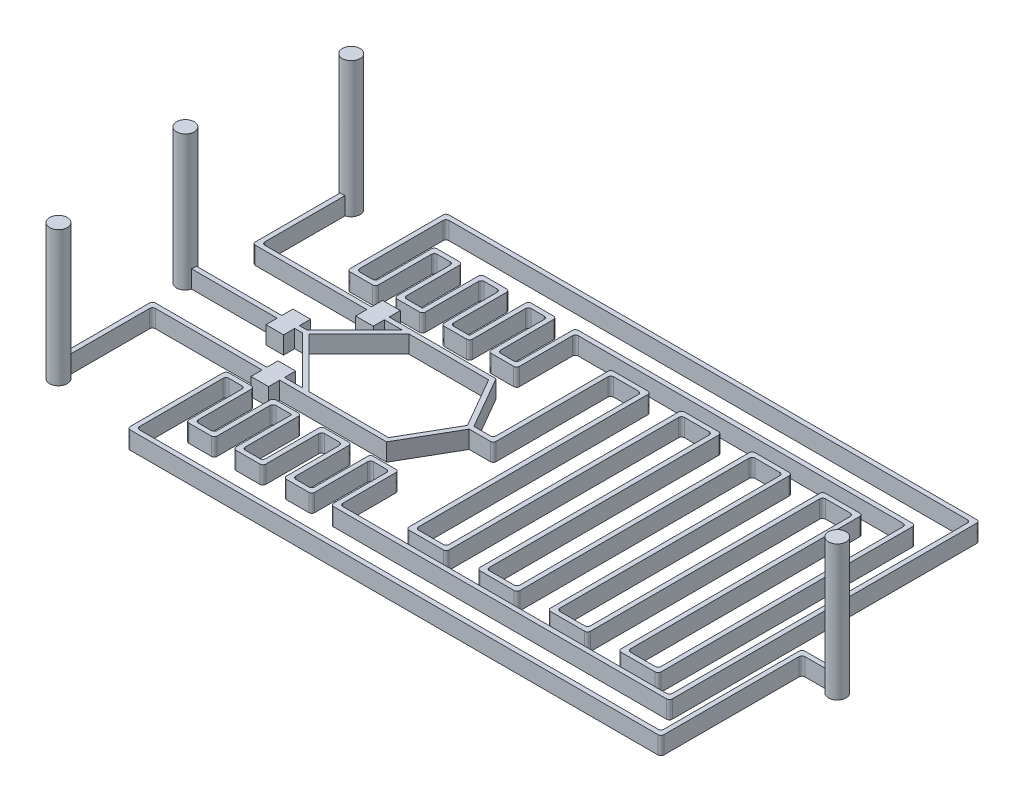
SolidWorks part; units mm, degrees
ref_plane "Front Plane" through (0, 0, 0) normal (0, 0, 1) x (1, 0, 0)
ref_plane "Top Plane" through (0, 0, 0) normal (0, 1, 0) x (1, 0, 0)
ref_plane "Right Plane" through (0, 0, 0) normal (1, 0, 0) x (0, 0, -1)
sketch "Sketch3" plane through (0, 0, 0) normal (0, 1, 0) x (1, 0, 0)
  line L0 (-37.0734, 0) -> (26.9266, 0) construction
  line L1 (19.9441, -2.9275) -> (19.9441, -14.4275)
  line L35 (-15.5329, 9.0171) -> (-23.3329, 9.0171) construction
  line L68 (-24.0079, 5.6024) -> (-22.5079, 5.6024)
  line L69 (-24.0079, 5.6024) -> (-24.0079, 4.6524)
  line L70 (-24.0079, 3.3024) -> (-22.5079, 3.3024)
  line L71 (-22.5079, 5.6024) -> (-22.5079, 4.6524)
  line L72 (-24.0079, 4.2524) -> (-24.0079, 3.3024)
  line L73 (-22.5079, 4.2524) -> (-22.5079, 3.3024)
  line L74 (-24.0079, -3.3024) -> (-22.5079, -3.3024)
  line L75 (-24.0079, -3.3024) -> (-24.0079, -4.2524)
  line L76 (-24.0079, -5.6024) -> (-22.5079, -5.6024)
  line L77 (-22.5079, -3.3024) -> (-22.5079, -4.2524)
  line L78 (-22.5079, -4.6524) -> (-22.5079, -5.6024)
  line L79 (-24.0079, -4.6524) -> (-24.0079, -5.6024)
  line L80 (-22.5079, -4.2524) -> (-20.9907, -4.2524)
  line L81 (-7.0734, 0) -> (26.9266, 0) construction
  line L82 (-13.4155, 4.6524) -> (-10.8448, 0.2)
  line L83 (-27.1856, 1.15) -> (-25.6856, 1.15)
  line L84 (-27.1856, 1.15) -> (-27.1856, 0.2)
  line L85 (-27.1856, -1.15) -> (-25.6856, -1.15)
  line L86 (-25.6856, 1.15) -> (-25.6856, 0.2)
  line L89 (-33.0809, 4.6524) -> (-24.0079, 4.6524)
  line L90 (-33.3309, 4.9024) -> (-33.3309, 11.7296)
  line L91 (-33.3309, -4.9024) -> (-33.3309, -11.7296)
  line L92 (-33.0809, -4.6524) -> (-24.0079, -4.6524)
  line L93 (-13.4155, -4.6524) -> (-10.8448, -0.2)
  line L94 (-10.8448, -0.2) -> (-9.05, -0.2)
  line L95 (-8.8, 0.05) -> (-8.8, 9.55)
  line L96 (-8.55, 9.8) -> (-6.45, 9.8)
  line L97 (-6.2, 9.55) -> (-6.2, 0)
  line L98 (-6.2, 0) -> (-6.2, -9.95)
  line L99 (-5.95, -10.2) -> (-3.05, -10.2)
  line L100 (-2.8, -9.95) -> (-2.8, 9.5671)
  line L101 (-2.55, 9.8171) -> (-0.45, 9.8171)
  line L102 (-0.2, 9.5671) -> (-0.2, -9.9275)
  line L103 (0.05, -10.1775) -> (2.95, -10.1775)
  line L104 (3.2, -9.9275) -> (3.2, 9.5725)
  line L105 (3.45, 9.8225) -> (5.55, 9.8225)
  line L106 (5.8, 9.5725) -> (5.8, -9.9275)
  line L107 (6.05, -10.1775) -> (8.95, -10.1775)
  line L108 (9.2, -9.9275) -> (9.2, 9.5725)
  line L109 (9.45, 9.8225) -> (11.55, 9.8225)
  line L110 (11.8, 9.5725) -> (11.8, -9.9275)
  line L111 (12.05, -10.1775) -> (14.95, -10.1775)
  line L112 (15.2, -9.9275) -> (15.2, 0)
  line L113 (15.2, 0) -> (15.2, 11.4671)
  line L114 (14.95, 11.7171) -> (-13.4809, 11.7171)
  line L115 (-13.7309, 11.4671) -> (-13.7309, 6.9671)
  line L116 (-13.9809, 6.7171) -> (-15.0829, 6.7171)
  line L117 (-15.3329, 6.9671) -> (-15.3329, 11.4671)
  line L118 (-15.5829, 11.7171) -> (-17.4829, 11.7171)
  line L119 (-17.7329, 11.4671) -> (-17.7329, 6.7171)
  line L120 (-17.7329, 6.7171) -> (-19.0829, 6.7171)
  line L121 (-19.3329, 6.9671) -> (-19.3329, 11.4671)
  line L122 (-19.5829, 11.7171) -> (-21.4829, 11.7171)
  line L123 (-21.7329, 11.4671) -> (-21.7329, 6.7171)
  line L124 (-21.7329, 6.7171) -> (-23.0829, 6.7171)
  line L125 (-23.3329, 6.9671) -> (-23.3329, 11.4671)
  line L126 (-23.5829, 11.7171) -> (-25.4829, 11.7171)
  line L127 (-25.7329, 11.4671) -> (-25.7329, 6.9671)
  line L128 (-25.9829, 6.7171) -> (-27.0829, 6.7171)
  line L129 (-27.3329, 6.9671) -> (-27.3329, 14.0671)
  line L130 (-27.0829, 14.3171) -> (17.0171, 14.3171)
  line L131 (17.2671, 14.0671) -> (17.2671, -11.0275)
  line L132 (17.0171, -11.2775) -> (-10.5103, -11.2775)
  line L133 (-10.7603, -11.0275) -> (-10.7603, -6.5275)
  line L134 (-11.0103, -6.2775) -> (-12.9103, -6.2775)
  line L135 (-13.1603, -6.5275) -> (-13.1603, -11.0275)
  line L136 (-13.4103, -11.2775) -> (-14.5103, -11.2775)
  line L137 (-14.7603, -11.0275) -> (-14.7603, -6.5275)
  line L138 (-15.0103, -6.2775) -> (-17.0705, -6.2775)
  line L139 (-17.3205, -6.5275) -> (-17.3205, -11.0275)
  line L140 (-17.5705, -11.2775) -> (-18.8059, -11.2775)
  line L141 (-19.0559, -11.0275) -> (-19.0559, -6.5275)
  line L142 (-19.3059, -6.2775) -> (-21.2059, -6.2775)
  line L143 (-21.4559, -6.5275) -> (-21.4559, -11.0275)
  line L144 (-21.7059, -11.2775) -> (-22.8059, -11.2775)
  line L145 (-23.0559, -11.0275) -> (-23.0559, -6.5275)
  line L146 (-23.3059, -6.2775) -> (-25.2059, -6.2775)
  line L147 (-25.4559, -6.5275) -> (-25.4559, -14.4275)
  line L148 (-25.2059, -14.6775) -> (19.6941, -14.6775)
  line L149 (-24.6775, 0) -> (-20.425, 4.2524)
  line L150 (-25.0432, -0.2) -> (-20.9907, -4.2524)
  line L151 (-13.6464, 4.2524) -> (-11.1913, 0)
  line L152 (-33.4809, 4.2524) -> (-24.0079, 4.2524)
  line L153 (-33.7309, 4.5024) -> (-33.7309, 11.7296)
  line L154 (-33.7309, -4.5024) -> (-33.7309, -11.7296)
  line L155 (-33.4809, -4.2524) -> (-24.0079, -4.2524)
  line L156 (-13.6464, -4.2524) -> (-11.1913, 0)
  line L157 (-10.8448, 0.2) -> (-9.45, 0.2)
  line L158 (-9.2, 0.45) -> (-9.2, 9.95)
  line L159 (-8.95, 10.2) -> (-6.05, 10.2)
  line L160 (-5.8, 9.95) -> (-5.8, 0)
  line L161 (-5.8, 0) -> (-5.8, -9.55)
  line L162 (-5.55, -9.8) -> (-3.45, -9.8)
  line L163 (-3.2, -9.55) -> (-3.2, 9.9671)
  line L164 (-2.95, 10.2171) -> (-0.05, 10.2171)
  line L165 (0.2, 9.9671) -> (0.2, -9.5275)
  line L166 (0.45, -9.7775) -> (2.55, -9.7775)
  line L167 (2.8, -9.5275) -> (2.8, 9.9725)
  line L168 (3.05, 10.2225) -> (5.95, 10.2225)
  line L169 (6.2, 9.9725) -> (6.2, -9.5275)
  line L170 (6.45, -9.7775) -> (8.55, -9.7775)
  line L171 (8.8, -9.5275) -> (8.8, 9.9725)
  line L172 (9.05, 10.2225) -> (11.95, 10.2225)
  line L173 (12.2, 9.9725) -> (12.2, -9.5275)
  line L174 (12.45, -9.7775) -> (14.55, -9.7775)
  line L175 (14.8, -9.5275) -> (14.8, 0)
  line L176 (14.8, 0) -> (14.8, 11.0671)
  line L177 (14.55, 11.3171) -> (-13.0809, 11.3171)
  line L178 (-13.3309, 11.0671) -> (-13.3309, 6.5671)
  line L179 (-13.5809, 6.3171) -> (-15.4829, 6.3171)
  line L180 (-15.7329, 6.5671) -> (-15.7329, 11.0671)
  line L181 (-15.9829, 11.3171) -> (-17.0829, 11.3171)
  line L182 (-17.3329, 11.0671) -> (-17.3329, 6.5671)
  line L183 (-17.5829, 6.3171) -> (-19.4829, 6.3171)
  line L184 (-19.7329, 6.5671) -> (-19.7329, 11.0671)
  line L185 (-19.9829, 11.3171) -> (-21.0829, 11.3171)
  line L186 (-21.3329, 11.0671) -> (-21.3329, 6.5671)
  line L187 (-21.5829, 6.3171) -> (-23.4829, 6.3171)
  line L188 (-23.7329, 6.5671) -> (-23.7329, 11.0671)
  line L189 (-23.9829, 11.3171) -> (-25.0829, 11.3171)
  line L190 (-25.3329, 11.0671) -> (-25.3329, 6.5671)
  line L191 (-25.5829, 6.3171) -> (-27.4829, 6.3171)
  line L192 (-27.7329, 6.5671) -> (-27.7329, 14.4671)
  line L193 (-27.4829, 14.7171) -> (17.4171, 14.7171)
  line L194 (17.6671, 14.4671) -> (17.6671, -11.4275)
  line L195 (17.4171, -11.6775) -> (-10.9103, -11.6775)
  line L196 (-11.1603, -11.4275) -> (-11.1603, -6.9275)
  line L197 (-11.4103, -6.6775) -> (-12.5103, -6.6775)
  line L198 (-12.7603, -6.9275) -> (-12.7603, -11.4275)
  line L199 (-13.0103, -11.6775) -> (-14.9103, -11.6775)
  line L200 (-15.1603, -11.4275) -> (-15.1603, -6.9275)
  line L201 (-15.4103, -6.6775) -> (-16.6705, -6.6775)
  line L202 (-16.9205, -6.9275) -> (-16.9205, -11.4275)
  line L203 (-17.1705, -11.6775) -> (-19.2059, -11.6775)
  line L204 (-19.4559, -11.4275) -> (-19.4559, -6.6775)
  line L205 (-19.4559, -6.6775) -> (-20.8059, -6.6775)
  line L206 (-21.0559, -6.9275) -> (-21.0559, -11.4275)
  line L207 (-21.3059, -11.6775) -> (-23.2059, -11.6775)
  line L208 (-23.4559, -11.4275) -> (-23.4559, -6.9275)
  line L209 (-23.7059, -6.6775) -> (-24.8059, -6.6775)
  line L210 (-25.0559, -6.9275) -> (-25.0559, -14.0275)
  line L211 (-24.8059, -14.2775) -> (19.2941, -14.2775)
  line L212 (-25.0432, 0.2) -> (-20.9907, 4.2524)
  line L213 (-24.6775, 0) -> (-20.425, -4.2524)
  line L217 (-25.6856, -0.2) -> (-25.0432, -0.2)
  line L218 (-27.1856, 0.2) -> (-34.4627, 0.2)
  line L220 (20.1941, -2.6775) -> (22.0212, -2.6775)
  line L221 (-25.6856, 0.2) -> (-25.0432, 0.2)
  line L222 (-27.1856, -0.2) -> (-34.4627, -0.2)
  line L223 (19.5441, -14.0275) -> (19.5441, -2.5275)
  line L224 (19.7941, -2.2775) -> (22.0212, -2.2775)
  line L229 (-22.5079, 4.6524) -> (-13.4155, 4.6524)
  line L231 (-22.5079, 4.2524) -> (-20.9907, 4.2524)
  line L233 (-20.425, 4.2524) -> (-13.6464, 4.2524)
  line L235 (-27.1856, -0.2) -> (-27.1856, -1.15)
  line L236 (-25.6856, -0.2) -> (-25.6856, -1.15)
  line L239 (-22.5079, -4.6524) -> (-13.4155, -4.6524)
  line L242 (-20.425, -4.2524) -> (-13.6464, -4.2524)
  arc A0 (-33.3309, 11.7296) -> (-33.7309, 11.7296) centre (-33.5309, 12.4524) ccw
  arc A1 (-34.4627, 0.2) -> (-34.4627, -0.2) centre (-35.1856, 0) ccw
  arc A2 (-33.7309, -11.7296) -> (-33.3309, -11.7296) centre (-33.5309, -12.4524) ccw
  arc A3 (22.0212, -2.6775) -> (22.0212, -2.2775) centre (22.7441, -2.4775) ccw
  arc A4 (11.8, -9.9275) -> (12.05, -10.1775) centre (12.05, -9.9275) ccw
  arc A5 (12.2, -9.5275) -> (12.45, -9.7775) centre (12.45, -9.5275) ccw
  arc A6 (14.95, -10.1775) -> (15.2, -9.9275) centre (14.95, -9.9275) ccw
  arc A7 (14.55, -9.7775) -> (14.8, -9.5275) centre (14.55, -9.5275) ccw
  arc A8 (19.5441, -2.5275) -> (19.7941, -2.2775) centre (19.7941, -2.5275) cw
  arc A9 (19.9441, -2.9275) -> (20.1941, -2.6775) centre (20.1941, -2.9275) cw
  arc A10 (17.6671, -11.4275) -> (17.4171, -11.6775) centre (17.4171, -11.4275) cw
  arc A11 (17.2671, -11.0275) -> (17.0171, -11.2775) centre (17.0171, -11.0275) cw
  arc A12 (17.4171, 14.7171) -> (17.6671, 14.4671) centre (17.4171, 14.4671) cw
  arc A13 (17.0171, 14.3171) -> (17.2671, 14.0671) centre (17.0171, 14.0671) cw
  arc A14 (15.2, 11.4671) -> (14.95, 11.7171) centre (14.95, 11.4671) ccw
  arc A15 (14.8, 11.0671) -> (14.55, 11.3171) centre (14.55, 11.0671) ccw
  arc A16 (-13.4809, 11.7171) -> (-13.7309, 11.4671) centre (-13.4809, 11.4671) ccw
  arc A17 (-13.0809, 11.3171) -> (-13.3309, 11.0671) centre (-13.0809, 11.0671) ccw
  arc A18 (-13.3309, 6.5671) -> (-13.5809, 6.3171) centre (-13.5809, 6.5671) cw
  arc A19 (-13.7309, 6.9671) -> (-13.9809, 6.7171) centre (-13.9809, 6.9671) cw
  arc A20 (-15.7329, 11.0671) -> (-15.9829, 11.3171) centre (-15.9829, 11.0671) ccw
  arc A21 (-15.3329, 11.4671) -> (-15.5829, 11.7171) centre (-15.5829, 11.4671) ccw
  arc A22 (-17.0829, 11.3171) -> (-17.3329, 11.0671) centre (-17.0829, 11.0671) ccw
  arc A23 (-17.4829, 11.7171) -> (-17.7329, 11.4671) centre (-17.4829, 11.4671) ccw
  arc A24 (-19.3329, 11.4671) -> (-19.5829, 11.7171) centre (-19.5829, 11.4671) ccw
  arc A25 (-19.7329, 11.0671) -> (-19.9829, 11.3171) centre (-19.9829, 11.0671) ccw
  arc A26 (-21.0829, 11.3171) -> (-21.3329, 11.0671) centre (-21.0829, 11.0671) ccw
  arc A27 (-21.4829, 11.7171) -> (-21.7329, 11.4671) centre (-21.4829, 11.4671) ccw
  arc A28 (-23.3329, 11.4671) -> (-23.5829, 11.7171) centre (-23.5829, 11.4671) ccw
  arc A29 (-23.7329, 11.0671) -> (-23.9829, 11.3171) centre (-23.9829, 11.0671) ccw
  arc A30 (-25.0829, 11.3171) -> (-25.3329, 11.0671) centre (-25.0829, 11.0671) ccw
  arc A31 (-25.4829, 11.7171) -> (-25.7329, 11.4671) centre (-25.4829, 11.4671) ccw
  arc A32 (-25.9829, 6.7171) -> (-25.7329, 6.9671) centre (-25.9829, 6.9671) ccw
  arc A33 (-25.3329, 6.5671) -> (-25.5829, 6.3171) centre (-25.5829, 6.5671) cw
  arc A34 (-33.7309, -4.5024) -> (-33.4809, -4.2524) centre (-33.4809, -4.5024) cw
  arc A35 (-33.3309, -4.9024) -> (-33.0809, -4.6524) centre (-33.0809, -4.9024) cw
  arc A36 (-14.9103, -11.6775) -> (-15.1603, -11.4275) centre (-14.9103, -11.4275) cw
  arc A37 (-14.5103, -11.2775) -> (-14.7603, -11.0275) centre (-14.5103, -11.0275) cw
  arc A38 (-13.4103, -11.2775) -> (-13.1603, -11.0275) centre (-13.4103, -11.0275) ccw
  arc A39 (-13.0103, -11.6775) -> (-12.7603, -11.4275) centre (-13.0103, -11.4275) ccw
  arc A40 (-10.9103, -11.6775) -> (-11.1603, -11.4275) centre (-10.9103, -11.4275) cw
  arc A41 (-10.5103, -11.2775) -> (-10.7603, -11.0275) centre (-10.5103, -11.0275) cw
  arc A42 (-25.4559, -6.5275) -> (-25.2059, -6.2775) centre (-25.2059, -6.5275) cw
  arc A43 (-25.0559, -6.9275) -> (-24.8059, -6.6775) centre (-24.8059, -6.9275) cw
  arc A44 (-23.0559, -6.5275) -> (-23.3059, -6.2775) centre (-23.3059, -6.5275) ccw
  arc A45 (-23.4559, -6.9275) -> (-23.7059, -6.6775) centre (-23.7059, -6.9275) ccw
  arc A46 (-11.1603, -6.9275) -> (-11.4103, -6.6775) centre (-11.4103, -6.9275) ccw
  arc A47 (-10.7603, -6.5275) -> (-11.0103, -6.2775) centre (-11.0103, -6.5275) ccw
  arc A48 (-13.1603, -6.5275) -> (-12.9103, -6.2775) centre (-12.9103, -6.5275) cw
  arc A49 (-12.7603, -6.9275) -> (-12.5103, -6.6775) centre (-12.5103, -6.9275) cw
  arc A50 (-14.7603, -6.5275) -> (-15.0103, -6.2775) centre (-15.0103, -6.5275) ccw
  arc A51 (-15.4103, -6.6775) -> (-15.1603, -6.9275) centre (-15.4103, -6.9275) cw
  arc A52 (-16.9205, -6.9275) -> (-16.6705, -6.6775) centre (-16.6705, -6.9275) cw
  arc A53 (-17.3205, -6.5275) -> (-17.0705, -6.2775) centre (-17.0705, -6.5275) cw
  arc A54 (-19.0559, -6.5275) -> (-19.3059, -6.2775) centre (-19.3059, -6.5275) ccw
  arc A55 (-21.4559, -6.5275) -> (-21.2059, -6.2775) centre (-21.2059, -6.5275) cw
  arc A56 (-21.0559, -6.9275) -> (-20.8059, -6.6775) centre (-20.8059, -6.9275) cw
  arc A57 (-23.2059, -11.6775) -> (-23.4559, -11.4275) centre (-23.2059, -11.4275) cw
  arc A58 (-22.8059, -11.2775) -> (-23.0559, -11.0275) centre (-22.8059, -11.0275) cw
  arc A59 (-21.4559, -11.0275) -> (-21.7059, -11.2775) centre (-21.7059, -11.0275) cw
  arc A60 (-21.3059, -11.6775) -> (-21.0559, -11.4275) centre (-21.3059, -11.4275) ccw
  arc A61 (-19.4559, -11.4275) -> (-19.2059, -11.6775) centre (-19.2059, -11.4275) ccw
  arc A62 (-17.1705, -11.6775) -> (-16.9205, -11.4275) centre (-17.1705, -11.4275) ccw
  arc A63 (-17.5705, -11.2775) -> (-17.3205, -11.0275) centre (-17.5705, -11.0275) ccw
  arc A64 (-18.8059, -11.2775) -> (-19.0559, -11.0275) centre (-18.8059, -11.0275) cw
  arc A65 (12.2, 9.9725) -> (11.95, 10.2225) centre (11.95, 9.9725) ccw
  arc A66 (11.8, 9.5725) -> (11.55, 9.8225) centre (11.55, 9.5725) ccw
  arc A67 (9.05, 10.2225) -> (8.8, 9.9725) centre (9.05, 9.9725) ccw
  arc A68 (9.45, 9.8225) -> (9.2, 9.5725) centre (9.45, 9.5725) ccw
  arc A69 (6.2, 9.9725) -> (5.95, 10.2225) centre (5.95, 9.9725) ccw
  arc A70 (5.8, 9.5725) -> (5.55, 9.8225) centre (5.55, 9.5725) ccw
  arc A71 (3.2, 9.5725) -> (3.45, 9.8225) centre (3.45, 9.5725) cw
  arc A72 (3.05, 10.2225) -> (2.8, 9.9725) centre (3.05, 9.9725) ccw
  arc A73 (-5.8, 9.95) -> (-6.05, 10.2) centre (-6.05, 9.95) ccw
  arc A74 (-6.45, 9.8) -> (-6.2, 9.55) centre (-6.45, 9.55) cw
  arc A75 (0.2, 9.9671) -> (-0.05, 10.2171) centre (-0.05, 9.9671) ccw
  arc A76 (-0.2, 9.5671) -> (-0.45, 9.8171) centre (-0.45, 9.5671) ccw
  arc A77 (-2.8, 9.5671) -> (-2.55, 9.8171) centre (-2.55, 9.5671) cw
  arc A78 (-3.2, 9.9671) -> (-2.95, 10.2171) centre (-2.95, 9.9671) cw
  arc A79 (-9.2, 9.95) -> (-8.95, 10.2) centre (-8.95, 9.95) cw
  arc A80 (-8.8, 9.55) -> (-8.55, 9.8) centre (-8.55, 9.55) cw
  arc A81 (8.95, -10.1775) -> (9.2, -9.9275) centre (8.95, -9.9275) ccw
  arc A82 (8.55, -9.7775) -> (8.8, -9.5275) centre (8.55, -9.5275) ccw
  arc A83 (6.05, -10.1775) -> (5.8, -9.9275) centre (6.05, -9.9275) cw
  arc A84 (6.45, -9.7775) -> (6.2, -9.5275) centre (6.45, -9.5275) cw
  arc A85 (2.95, -10.1775) -> (3.2, -9.9275) centre (2.95, -9.9275) ccw
  arc A86 (2.55, -9.7775) -> (2.8, -9.5275) centre (2.55, -9.5275) ccw
  arc A87 (0.45, -9.7775) -> (0.2, -9.5275) centre (0.45, -9.5275) cw
  arc A88 (0.05, -10.1775) -> (-0.2, -9.9275) centre (0.05, -9.9275) cw
  arc A89 (-3.05, -10.2) -> (-2.8, -9.95) centre (-3.05, -9.95) ccw
  arc A90 (-3.45, -9.8) -> (-3.2, -9.55) centre (-3.45, -9.55) ccw
  arc A91 (-6.2, -9.95) -> (-5.95, -10.2) centre (-5.95, -9.95) ccw
  arc A92 (-5.55, -9.8) -> (-5.8, -9.55) centre (-5.55, -9.55) cw
  arc A93 (-8.8, 0.05) -> (-9.05, -0.2) centre (-9.05, 0.05) cw
  arc A94 (-9.2, 0.45) -> (-9.45, 0.2) centre (-9.45, 0.45) cw
  arc A95 (-15.4829, 6.3171) -> (-15.7329, 6.5671) centre (-15.4829, 6.5671) cw
  arc A96 (-15.0829, 6.7171) -> (-15.3329, 6.9671) centre (-15.0829, 6.9671) cw
  arc A97 (-19.3329, 6.9671) -> (-19.0829, 6.7171) centre (-19.0829, 6.9671) ccw
  arc A98 (-19.4829, 6.3171) -> (-19.7329, 6.5671) centre (-19.4829, 6.5671) cw
  arc A99 (-23.7329, 6.5671) -> (-23.4829, 6.3171) centre (-23.4829, 6.5671) ccw
  arc A100 (-23.0829, 6.7171) -> (-23.3329, 6.9671) centre (-23.0829, 6.9671) cw
  arc A101 (-27.0829, 6.7171) -> (-27.3329, 6.9671) centre (-27.0829, 6.9671) cw
  arc A102 (-27.7329, 6.5671) -> (-27.4829, 6.3171) centre (-27.4829, 6.5671) ccw
  arc A103 (-33.4809, 4.2524) -> (-33.7309, 4.5024) centre (-33.4809, 4.5024) cw
  arc A104 (-33.0809, 4.6524) -> (-33.3309, 4.9024) centre (-33.0809, 4.9024) cw
  arc A105 (-27.7329, 14.4671) -> (-27.4829, 14.7171) centre (-27.4829, 14.4671) cw
  arc A106 (-27.3329, 14.0671) -> (-27.0829, 14.3171) centre (-27.0829, 14.0671) cw
  arc A107 (-17.5829, 6.3171) -> (-17.3329, 6.5671) centre (-17.5829, 6.5671) ccw
  arc A108 (-21.5829, 6.3171) -> (-21.3329, 6.5671) centre (-21.5829, 6.5671) ccw
  arc A109 (19.9441, -14.4275) -> (19.6941, -14.6775) centre (19.6941, -14.4275) cw
  arc A110 (19.2941, -14.2775) -> (19.5441, -14.0275) centre (19.2941, -14.0275) ccw
  arc A111 (-25.4559, -14.4275) -> (-25.2059, -14.6775) centre (-25.2059, -14.4275) ccw
  arc A112 (-25.0559, -14.0275) -> (-24.8059, -14.2775) centre (-24.8059, -14.0275) ccw
  point P24 (-37.0734, 0)
  point P27 (26.9266, 0)
  point P54 (-23.2579, 4.4524)
  point P72 (-23.2579, -4.4524)
  point P79 (-26.4356, 0)
  dimension "D10" = 1.5
  dimension "D11" = 1.5
  dimension "D12" = 1.5
  dimension "D26" = 1.5
  dimension "D27" = 0.25
  dimension "D3" = 0.25
  dimension "D4" = 0.25
  dimension "D5" = 0.25
  dimension "D13" = 1.5
  dimension "D14" = 2.3
  dimension "D15" = 1.5
  dimension "D16" = 2.3
  dimension "D17" = 2.3
  dimension "D18" = 1.5
extrude "Boss-Extrude1" add sketch "Sketch3" along normal blind 1.5
sketch "Sketch4" plane through (0, 1.5, 0) normal (0, 1, 0) x (1, 0, 0)
  circle A0 centre (22.7441, -2.4775) radius 0.75
  circle A1 centre (-33.5309, -12.4524) radius 0.75
  circle A2 centre (-35.1856, 0) radius 0.75
  circle A3 centre (-33.5309, 12.4524) radius 0.75
extrude "Boss-Extrude2" add sketch "Sketch4" along normal blind 10
